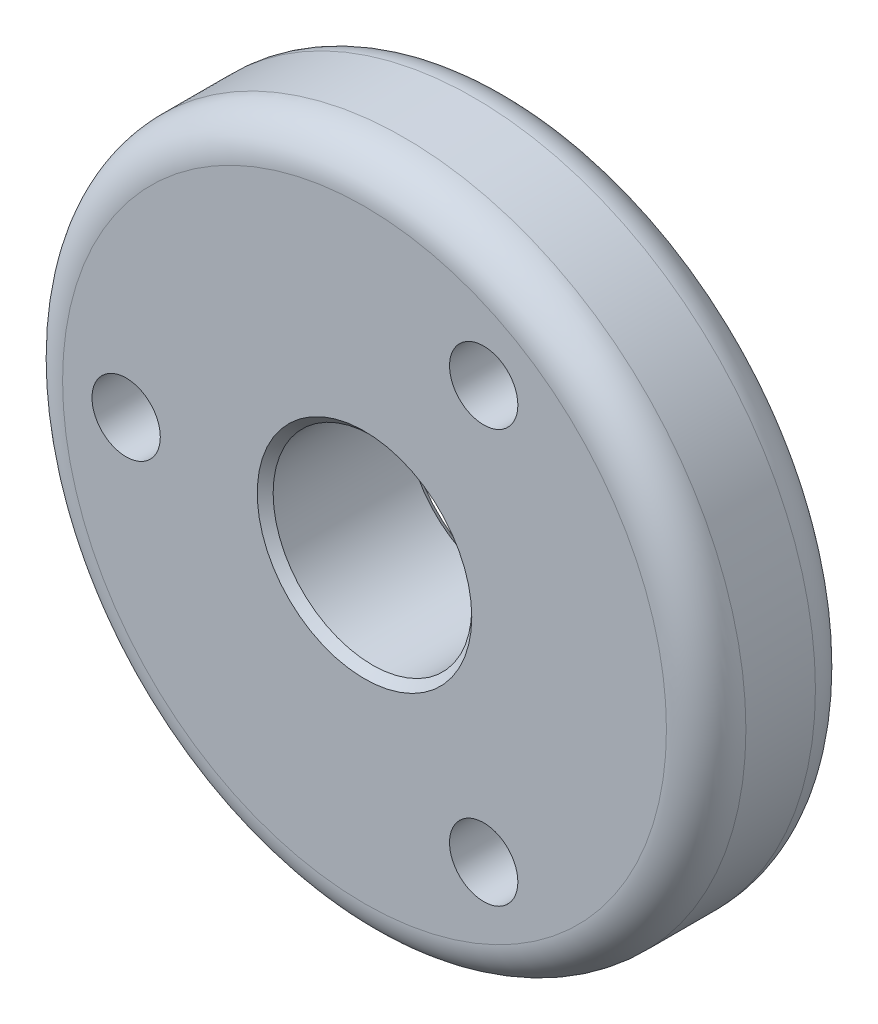
SolidWorks part; units mm, degrees
ref_plane "Front Plane" through (0, 0, 0) normal (0, 0, 1) x (1, 0, 0)
ref_plane "Top Plane" through (0, 0, 0) normal (0, 1, 0) x (1, 0, 0)
ref_plane "Right Plane" through (0, 0, 0) normal (1, 0, 0) x (0, 0, -1)
sketch "Sketch1" plane through (0, 0, 0) normal (0, 0, 1) x (1, 0, 0)
  circle A0 centre (0, 0) radius 1.5875
  circle A1 centre (0, 0) radius 5.461
  dimension "D1" = 3.175
  dimension "D2" = 10.922
extrude "Boss-Extrude1" add sketch "Sketch1" along normal mid plane 2.3813
fillet "Fillet1" radius 0.635 2 edges at (5.461, 0, -1.1906) (5.461, 0, 1.1906)
chamfer "Chamfer1" distance 0.127 2 edges at (1.5875, 0, -1.1906) (1.5875, 0, 1.1906)
sketch "Sketch2" plane through (0, 0, 1.1906) normal (0, 0, 1) x (1, 0, 0)
  circle A0 centre (-3.81, 0) radius 0.5461
  dimension "D1" = 1.0922
  dimension "D2" = 3.81
extrude "Cut-Extrude1" cut sketch "Sketch2" against normal through all
pattern_circular "CirPattern1" count 3 over 360 about axis through (0, 0, 0) along (0, 0, 1) of "Cut-Extrude1"
